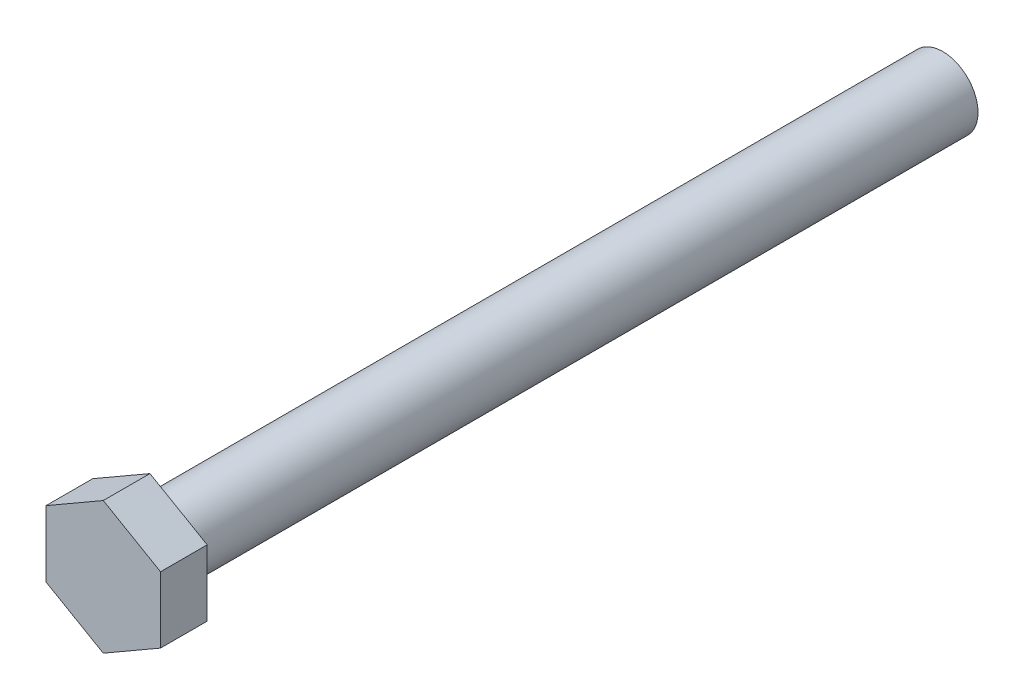
SolidWorks part; units mm, degrees
ref_plane "Спереди" through (0, 0, 0) normal (0, 0, 1) x (1, 0, 0)
ref_plane "Сверху" through (0, 0, 0) normal (0, 1, 0) x (1, 0, 0)
ref_plane "Справа" through (0, 0, 0) normal (1, 0, 0) x (0, 0, -1)
sketch "Эскиз1" plane through (0, 0, 0) normal (0, 0, 1) x (1, 0, 0)
  line L1 (0, 7.5056) -> (-6.5, 3.7528)
  line L2 (-6.5, 3.7528) -> (-6.5, -3.7528)
  line L3 (-6.5, -3.7528) -> (0, -7.5056)
  line L4 (0, -7.5056) -> (6.5, -3.7528)
  line L5 (6.5, -3.7528) -> (6.5, 3.7528)
  line L6 (6.5, 3.7528) -> (0, 7.5056)
  circle A0 centre (0, 0) radius 6.5 construction
  dimension "D1" = 13
extrude "Головка" add sketch "Эскиз1" along normal blind 5.3
sketch "Эскиз2" plane through (0, 0, 0) normal (0, 0, -1) x (-1, 0, 0)
  circle A0 centre (0, 0) radius 4
  dimension "D1" = 8
extrude "Болт" add sketch "Эскиз2" along normal blind 90
